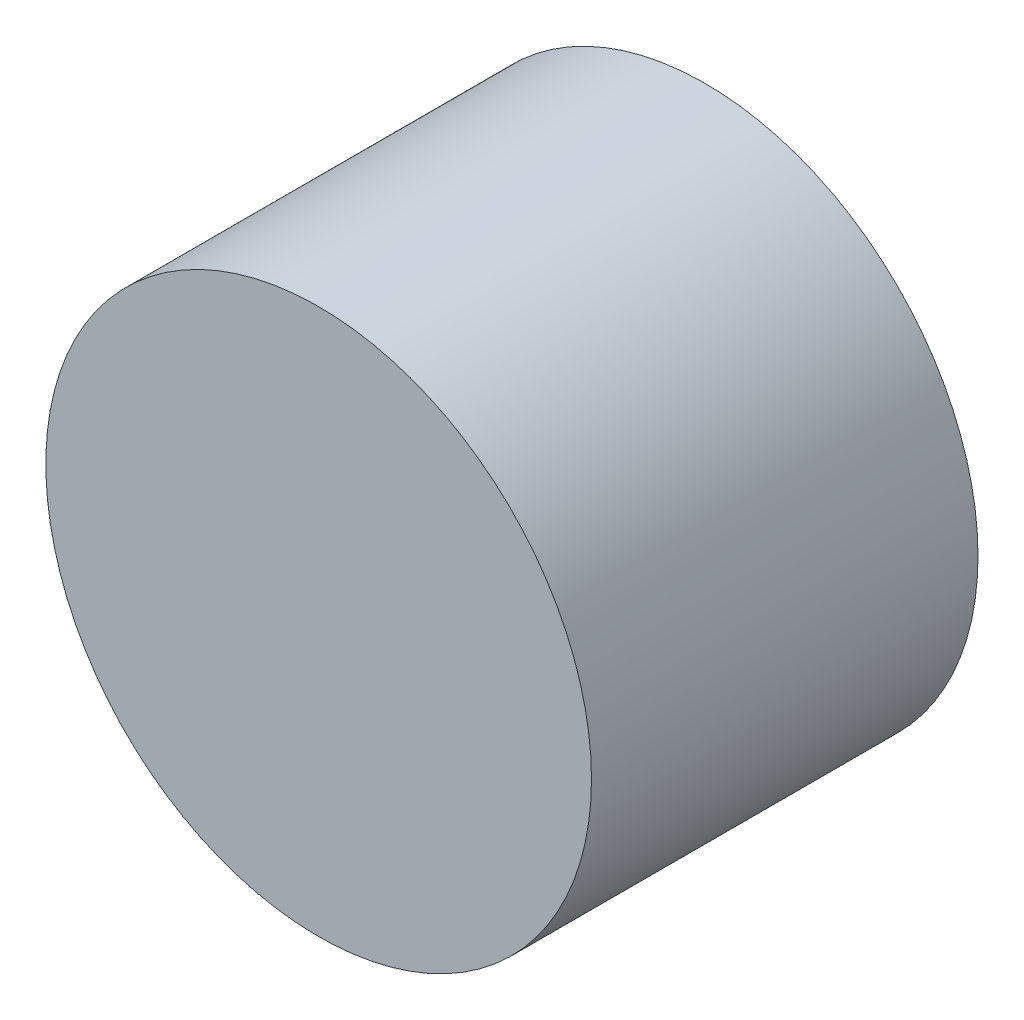
SolidWorks part; units mm, degrees
ref_plane "Ebene vorne" through (0, 0, 0) normal (0, 0, 1) x (1, 0, 0)
ref_plane "Ebene oben" through (0, 0, 0) normal (0, 1, 0) x (1, 0, 0)
ref_plane "Ebene rechts" through (0, 0, 0) normal (1, 0, 0) x (0, 0, -1)
sketch "Skizze1" plane through (0, 0, 0) normal (0, 0, 1) x (1, 0, 0)
  line L0 (-6, 6.2992) -> (6.5984, 6.2992) construction
  line L1 (6.5984, 6.2992) -> (6.5984, -6.2992) construction
  line L2 (6.5984, -6.2992) -> (-6, -6.2992) construction
  line L3 (-6, -6.2992) -> (-6, 6.2992) construction
  circle A0 centre (0, 0) radius 6
  dimension "D1" = 12
extrude "Component_Outline" add sketch "Skizze1" along normal blind 8.5 separate body
sketch3d "3D-Skizze1"
  line L0 (0, 0, 0) -> (1, 0, 0)
  line L1 (0, 0, 0) -> (0, 1, 0)
  line L2 (0, 0, 0) -> (0, 0, 1)
  point P0 (0, 0, 0)
sketch "Skizze2" plane through (0, 0, 0) normal (0, 0, -1) x (-1, 0, 0)
  circle A0 centre (-2.29, 0) radius 0.5
  dimension "D1" = 2.29
  dimension "D2" = 1
extrude "Aufsatz-Linear austragen1" add sketch "Skizze2" along normal blind 1.7
mirror "Spiegeln1" about plane through (0, 0, 0) normal (1, 0, 0) of "Aufsatz-Linear austragen1"
